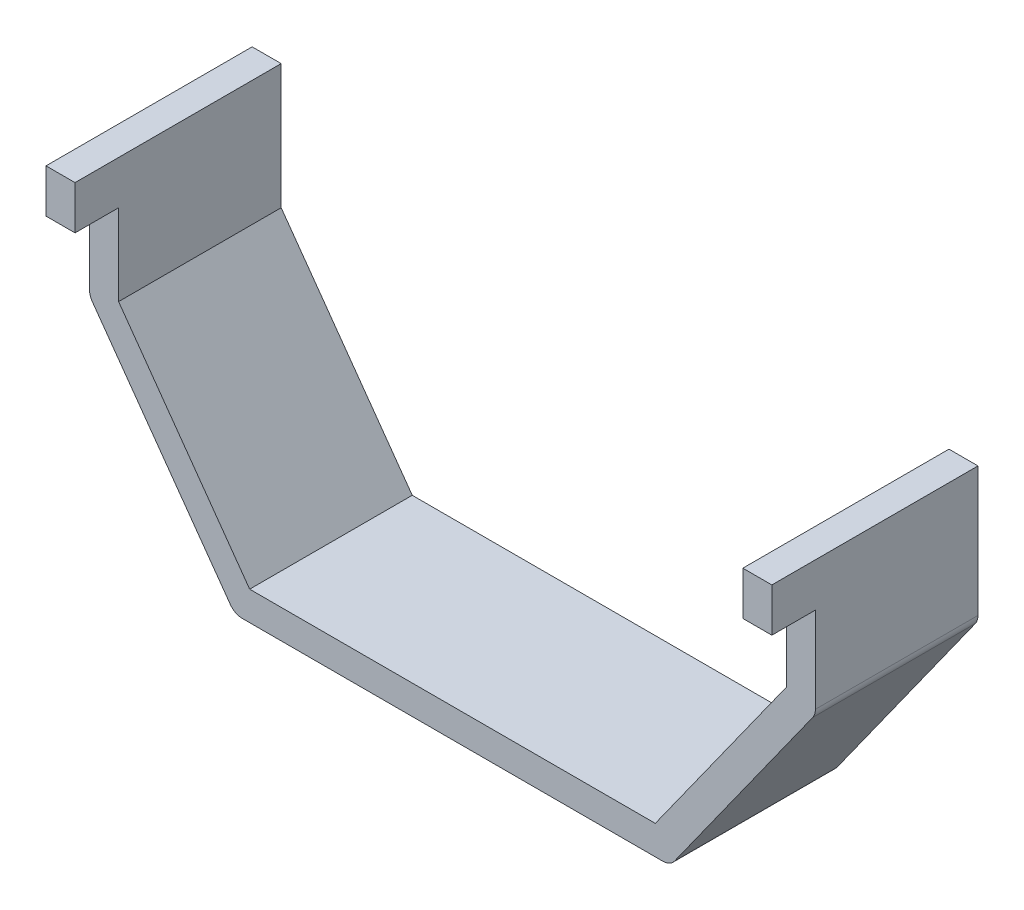
SolidWorks part; units mm, degrees
ref_plane "Plan de face" through (0, 0, 0) normal (0, 0, 1) x (1, 0, 0)
ref_plane "Plan de dessus" through (0, 0, 0) normal (0, 1, 0) x (1, 0, 0)
ref_plane "Plan de droite" through (0, 0, 0) normal (1, 0, 0) x (0, 0, -1)
sketch "Esquisse1" plane through (0, 0, 0) normal (0, 0, 1) x (1, 0, 0)
  line L0 (-124.9981, 116.1973) -> (-114.9981, 116.1973)
  line L6 (-124.9981, 116.1973) -> (-124.9981, 69.9973)
  line L8 (-124.9981, 69.9973) -> (-75, 0)
  line L9 (-75, 0) -> (75, 0)
  line L10 (75, 0) -> (125.0019, 69.9947)
  line L11 (125.0019, 69.9947) -> (125.0019, 116.1947)
  line L12 (125.0019, 116.1947) -> (115.0019, 116.1947)
  line L13 (115.0019, 116.1947) -> (115.0019, 73.1996)
  line L14 (115.0019, 73.1996) -> (69.8542, 10)
  line L15 (69.8542, 10) -> (-69.8538, 10)
  line L16 (-114.9981, 116.1973) -> (-114.9981, 73.202)
  line L17 (-114.9981, 73.202) -> (-69.8538, 10)
  point P0 (0, 0)
  dimension "D1" = 86.02
  dimension "D2" = 46.2
  dimension "D3" = 86.02
  dimension "D4" = 46.2
  dimension "D5" = 150
  dimension "D6" = 250
  dimension "D7" = 10
  dimension "D8" = 10
  dimension "D9" = 10
  dimension "D12" = 10
  dimension "D15" = 10
extrude "Boss.-Extru.1" add sketch "Esquisse1" along normal blind 71
sketch "Esquisse3" plane through (0, 0, 71) normal (0, 0, 1) x (1, 0, 0)
  line L0 (125.0019, 116.1947) -> (115.0019, 116.1947) construction
  line L1 (159.9808, -15.6948) -> (-164.9324, -15.6948)
  line L2 (159.9808, -15.6948) -> (159.9808, 101.1947)
  line L3 (159.9808, 101.1947) -> (-164.9324, 101.1947)
  line L4 (-164.9324, -15.6948) -> (-164.9324, 101.1947)
  dimension "D1" = 15
extrude "Enlèv. mat.-Extru.2" cut sketch "Esquisse3" against normal blind 15
fillet "Congé1" radius 5 4 edges at (-124.9981, 69.9973, 28) (-75, 0, 28) (75, 0, 28) (125.0019, 69.9947, 28)
sketch "Esquisse4" plane through (0, 0, 0) normal (0, 0, -1) x (-1, 0, 0)
  line L0 (-69.8542, 10) -> (69.8538, 10) construction
  line L2 (-76.4956, 2.0936) -> (-124.0704, 68.6907) construction
  line L3 (124.0668, 68.6935) -> (76.4956, 2.0938) construction
  line L4 (-125.0019, 116.1947) -> (-115.0019, 116.1947) construction
  line L5 (-125.0019, 71.5972) -> (-125.0019, 116.1947) construction
  line L6 (124.9981, 116.1973) -> (124.9981, 71.5997) construction
  line L7 (114.9981, 116.1973) -> (124.9981, 116.1973) construction
  circle A0 centre (-72.4271, 5) radius 2
  circle A1 centre (72.4269, 5) radius 2
  circle A2 centre (-120.0019, 111.1947) radius 2
  circle A3 centre (119.9981, 111.1973) radius 2
  dimension "D1" = 4
  dimension "D2" = 4
  dimension "D7" = 4
  dimension "D8" = 4
  dimension "D3" = 5
  dimension "D4" = 5
  dimension "D5" = 5
  dimension "D6" = 5
  dimension "D9" = 5
  dimension "D10" = 5
  dimension "D11" = 5
  dimension "D12" = 5
extrude "Enlèv. mat.-Extru.3" cut sketch "Esquisse4" against normal blind 8
